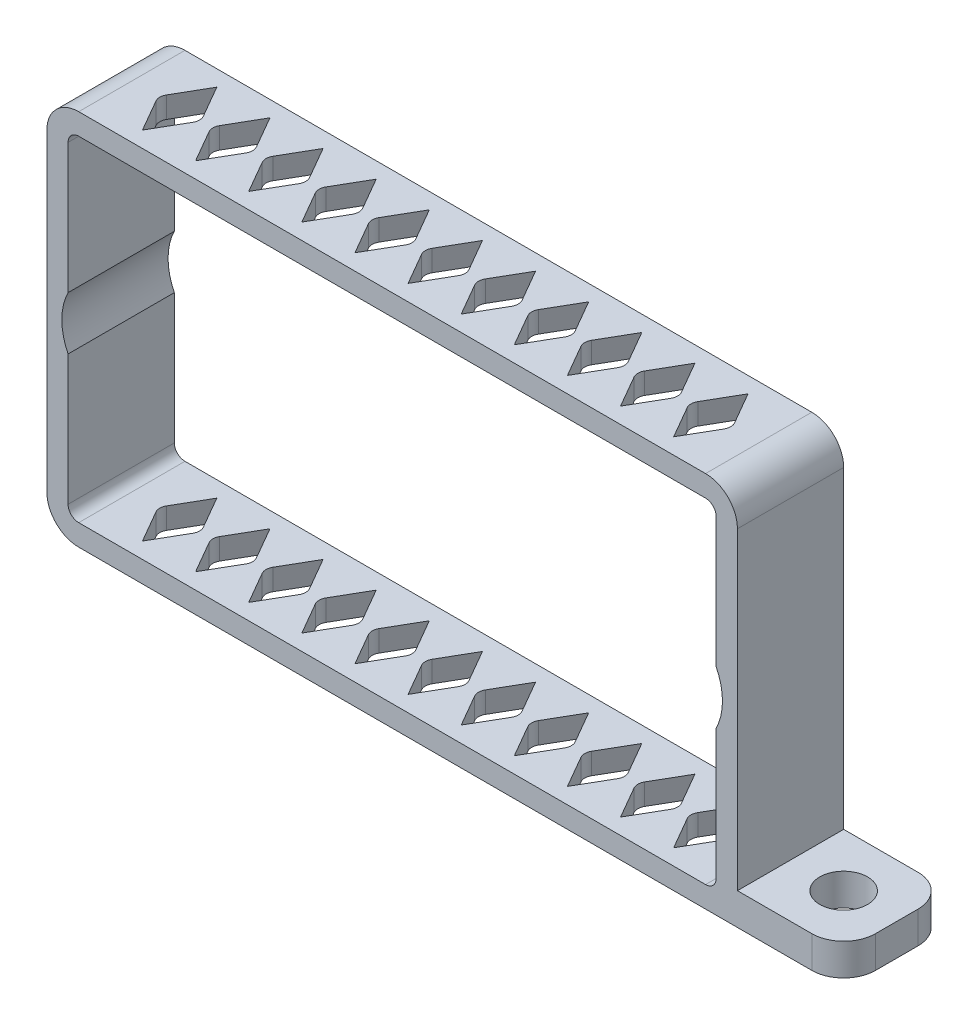
SolidWorks part; units mm, degrees
ref_plane "Front Plane" through (0, 0, 0) normal (0, 0, 1) x (1, 0, 0)
ref_plane "Top Plane" through (0, 0, 0) normal (0, 1, 0) x (1, 0, 0)
ref_plane "Right Plane" through (0, 0, 0) normal (1, 0, 0) x (0, 0, -1)
sketch "Sketch1" plane through (0, 0, 0) normal (0, 0, 1) x (1, 0, 0)
  line L0 (-32.5, -14.75) -> (-32.5, 14.75)
  line L5 (-29.5, -15.75) -> (29.5, -15.75)
  line L6 (-30.5, -14.75) -> (-30.5, -2.5)
  line L7 (-29.5, 15.75) -> (29.5, 15.75)
  line L8 (30.5, -14.75) -> (30.5, -2.5)
  line L9 (-30.5, -15.75) -> (30.5, 15.75) construction
  line L10 (-30.5, 15.75) -> (30.5, -15.75) construction
  line L11 (-29.5, 17.75) -> (29.5, 17.75)
  line L12 (32.5, -14.75) -> (32.5, 14.75)
  line L13 (-29.5, -17.75) -> (29.5, -17.75)
  line L14 (29.5, -17.75) -> (42.5, -17.75)
  line L15 (42.5, -17.75) -> (42.5, -14.75)
  line L16 (32.5, -14.75) -> (42.5, -14.75)
  line L17 (-30.5, 2.5) -> (-30.5, 14.75)
  line L18 (-30.5, -14.75) -> (-30.5, 14.75) construction
  line L19 (0, -55) -> (0, 55) construction
  line L20 (30.5, 2.5) -> (30.5, 14.75)
  line L21 (30.5, -14.75) -> (30.5, 14.75) construction
  arc A0 (-29.5, -15.75) -> (-30.5, -14.75) centre (-29.5, -14.75) cw
  arc A1 (29.5, -15.75) -> (30.5, -14.75) centre (29.5, -14.75) ccw
  arc A2 (29.5, 15.75) -> (30.5, 14.75) centre (29.5, 14.75) cw
  arc A3 (-30.5, 14.75) -> (-29.5, 15.75) centre (-29.5, 14.75) cw
  arc A4 (-32.5, 14.75) -> (-29.5, 17.75) centre (-29.5, 14.75) cw
  arc A5 (29.5, 17.75) -> (32.5, 14.75) centre (29.5, 14.75) cw
  arc A7 (-29.5, -17.75) -> (-32.5, -14.75) centre (-29.5, -14.75) cw
  arc A8 (29.5, -17.75) -> (32.5, -14.75) centre (29.5, -14.75) ccw construction
  arc A9 (-30.5, 2.5) -> (-30.5, -2.5) centre (-25.5, 0) ccw
  arc A10 (30.5, 2.5) -> (30.5, -2.5) centre (25.5, 0) cw
  point P0 (0, 0)
  dimension "D3" = 1
  dimension "D7" = 5
  dimension "D1" = 61
  dimension "D2" = 31.5
  dimension "D5" = 10
  dimension "D6" = 5
  dimension "D4" = 2
extrude "Boss-Extrude1" add sketch "Sketch1" along normal mid plane 10
sketch "Sketch2" plane through (0, -14.75, 0) normal (0, 1, 0) x (1, 0, 0)
  line L0 (42.5, 5) -> (32.5, 5) construction
  circle A0 centre (37.5, 0) radius 2.25
  point P5 (37.5, 5)
  dimension "D1" = 4.5
extrude "Cut-Extrude1" cut sketch "Sketch2" against normal through all
fillet "Fillet1" radius 3 2 edges at (42.5, -16.25, -5) (42.5, -16.25, 5)
sketch "Sketch3" plane through (0, -17.75, 0) normal (0, -1, 0) x (1, 0, 0)
  line L0 (0, -3.5) -> (1.7321, -0.5)
  line L1 (0, -3.5) -> (-1.7321, -0.5)
  line L2 (1.7321, 0.5) -> (0, 3.5)
  line L3 (-1.7321, 0.5) -> (0, 3.5)
  line L4 (0, -3.5) -> (0, 3.5) construction
  line L5 (2.0207, 0) -> (-2.0207, 0) construction
  line L8 (-29.5, 5) -> (39.5, 5) construction
  line L10 (0, 3.5) -> (0, 5) construction
  line L11 (0, -3.5) -> (0, -5) construction
  line L12 (-29.5, -5) -> (39.5, -5) construction
  arc A0 (1.7321, -0.5) -> (1.7321, 0.5) centre (0.866, 0) ccw
  arc A1 (-1.7321, -0.5) -> (-1.7321, 0.5) centre (-0.866, 0) cw
  point P1 (0, 0)
  point P12 (0, 0)
  point P13 (0, 0)
  dimension "D3" = 1
  dimension "D1" = 1.5
  dimension "D2" = 60
extrude "Cut-Extrude2" cut sketch "Sketch3" against normal through all
pattern_linear "LPattern1" count 6 spacing 5 along (-1, 0, 0) count 6 spacing 5 along (1, 0, 0) of "Cut-Extrude2"
